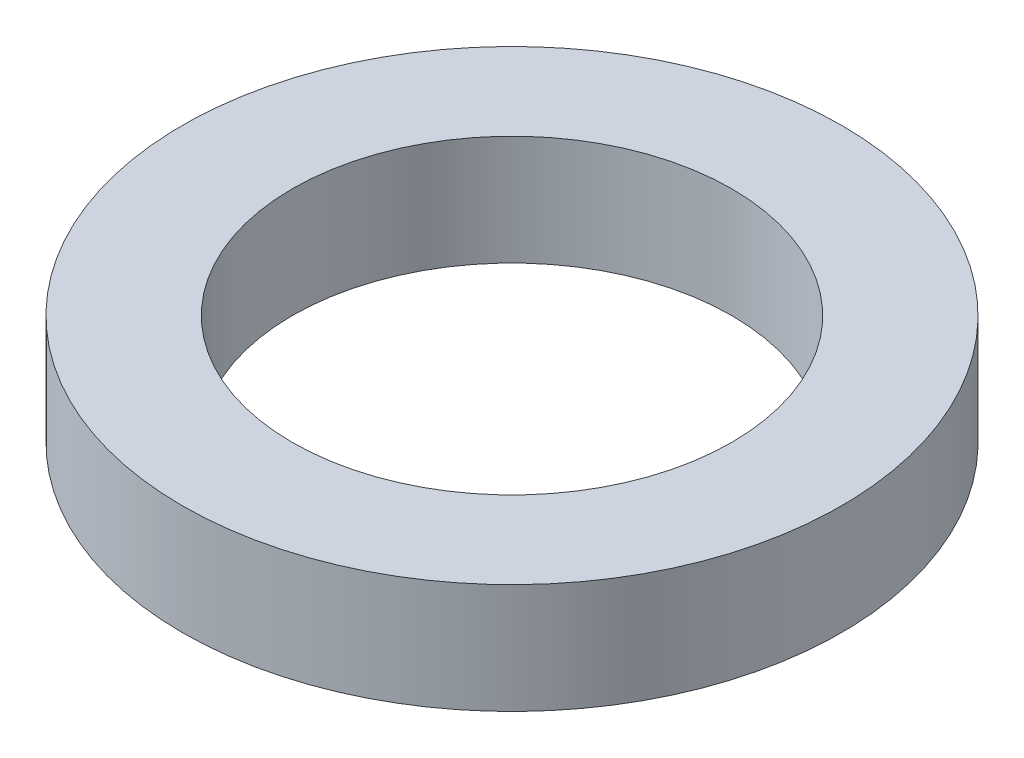
SolidWorks part; units mm, degrees
ref_plane "Front Plane" through (0, 0, 0) normal (0, 0, 1) x (1, 0, 0)
ref_plane "Top Plane" through (0, 0, 0) normal (0, 1, 0) x (1, 0, 0)
ref_plane "Right Plane" through (0, 0, 0) normal (1, 0, 0) x (0, 0, -1)
sketch "Sketch1" plane through (0, 0, 0) normal (0, 0, 1) x (1, 0, 0)
  line L0 (3.175, 1.5875) -> (3.175, 0)
  line L1 (3.175, 0) -> (4.7625, 0)
  line L2 (4.7625, 0) -> (4.7625, 1.5875)
  line L3 (4.7625, 1.5875) -> (3.175, 1.5875)
  line L4 (0, 1.5875) -> (0, 0) construction
revolve "Revolve1" add sketch "Sketch1" angle 360 about L4
